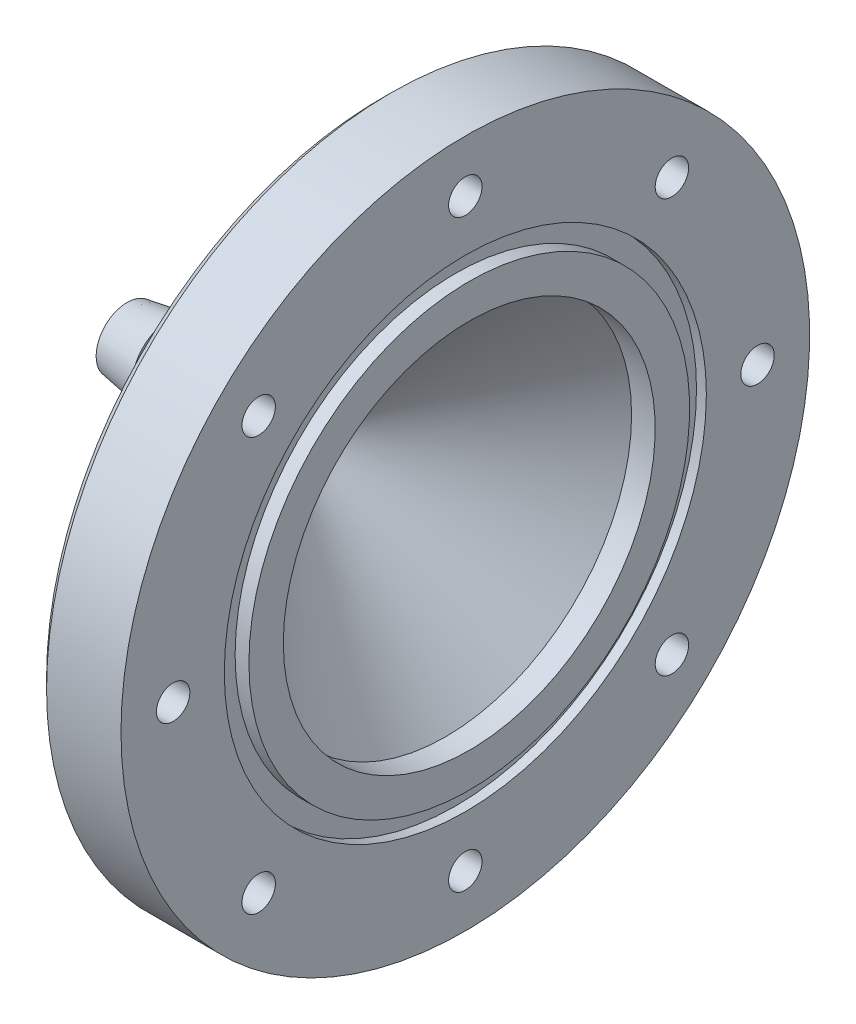
SolidWorks part; units mm, degrees
ref_plane "Front Plane" through (0, 0, 0) normal (0, 0, 1) x (1, 0, 0)
ref_plane "Top Plane" through (0, 0, 0) normal (0, 1, 0) x (1, 0, 0)
ref_plane "Right Plane" through (0, 0, 0) normal (1, 0, 0) x (0, 0, -1)
sketch "Sketch1" plane through (0, 0, 0) normal (0, 0, 1) x (1, 0, 0)
  line L0 (-801.9206, 0) -> (36107.5283, 0) construction
  line L3 (-13.5729, 3.85) -> (-13.5729, 3.15)
  line L8 (-17.9062, 1.9) -> (0, 1.9)
  line L9 (-17.9062, 1.9) -> (-17.9062, 3.15)
  line L10 (16.4699, 24.5) -> (16.4699, 35)
  line L12 (16.4699, 35) -> (7.9039, 35)
  line L16 (16.4699, 24.5) -> (15.4699, 24.5)
  line L17 (15.4699, 24.5) -> (15.4699, 18.9)
  line L18 (7.9039, 35) -> (7.9039, 18.9)
  line L20 (0, 1.9) -> (14.4699, 18.9)
  line L21 (-17.9062, 3.15) -> (-13.5729, 3.85)
  line L22 (14.4699, 18.9) -> (15.4699, 18.9)
  line L23 (-13.5729, 3.15) -> (-9.2395, 3.85)
  line L25 (-9.2395, 3.15) -> (-4.9062, 3.85)
  line L26 (-9.2395, 3.85) -> (-9.2395, 3.15)
  line L27 (-4.9062, 3.85) -> (7.9039, 18.9)
  line L33 (15.4699, 22.4) -> (16.8699, 22.4)
  line L34 (16.8699, 22.4) -> (16.8699, 18.9)
  line L35 (16.8699, 18.9) -> (15.4699, 18.9)
  dimension "D3" = 1
  dimension "D2" = 7.7
  dimension "D6" = 3.8
  dimension "D7" = 6.3
  dimension "D5" = 35
  dimension "D8" = 24.5
  dimension "D4" = 5
  dimension "D9" = 1
  dimension "D11" = 13
  dimension "D12" = 8.566
  dimension "D16" = 3.5
  dimension "D10" = 2.1
  dimension "D13" = 0.4
revolve "Revolve17" add sketch "Sketch1" angle 360 about L0
sketch "Sketch4" plane through (7.9039, 0, 0) normal (-1, 0, 0) x (0, 0, 1)
  line L0 (0, 18.9) -> (0, 35) construction
  circle A0 centre (0, 0) radius 29.7 construction
  circle A1 centre (0, 0) radius 18.9 construction
  circle A2 centre (0, 0) radius 35 construction
  point P3 (0, 29.7)
  point P7 (29.7, 0)
  point P12 (-29.7, 0)
  point P13 (0, -29.7)
  point P22 (-21.0011, 20.8472)
  point P25 (21.0011, 20.8472)
  point P28 (21.0011, -21.1549)
  point P31 (-21.0011, -21.1549)
  dimension "D1" = 5.3
  dimension "D2" = 5.3
hole_wizard "CBORE for M3 Hex Socket Head Cap Screw2" positions "Sketch4" profile "Sketch5" counterbore size "M3" standard "ISO"
sketch "Sketch5" plane through (7.9039, -21.1549, -21.0011) normal (0, 1, 0) x (0, 0, 1)
  line L0 (0, 0) -> (0, 9.5875)
  line L1 (0, 9.5875) -> (1.7, 8.566)
  line L2 (1.7, 8.566) -> (1.7, 3.4)
  line L3 (1.7, 3.4) -> (3.25, 3.4)
  line L4 (3.25, 3.4) -> (3.25, 0)
  line L5 (3.25, 0) -> (0, 0)
  line L10 (0, 9.5875) -> (-1.7, 8.566) construction
  line L11 (0, -6.35) -> (0, 107.95) construction
  dimension "Hole Dia." = 3.4
  dimension "Hole Depth" = 8.566
  dimension "C'Bore Dia." = 6.5
  dimension "C'Bore Depth" = 3.4
  dimension "Drill Angle" = 118
chamfer "Chamfer1" distance 1 angle 45 1 edges at (7.9039, 0, 35)
sketch "Sketch6" plane through (16.4699, 0, 0) normal (1, 0, 0) x (0, 0, -1)
  line L0 (0, 35) -> (0, 24.5)
  circle A0 centre (0, 0) radius 35
  circle A1 centre (0, 0) radius 35 construction
  circle A2 centre (0, 0) radius 24.5 construction
equation "\"D9@Sketch1\"=\"D3@Sketch1\""
